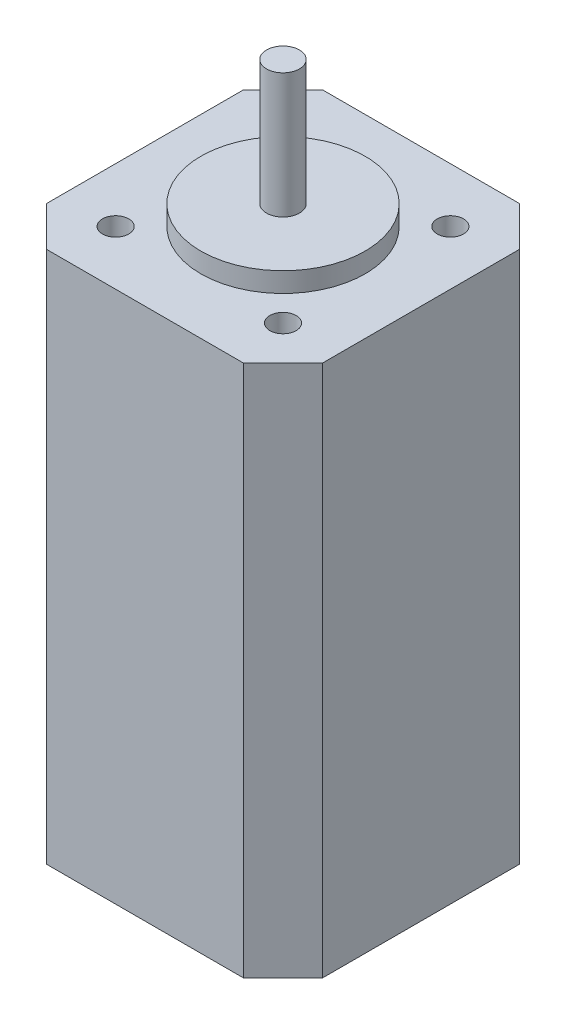
SolidWorks part; units mm, degrees
ref_plane "Płaszczyzna przednia" through (0, 0, 0) normal (0, 0, 1) x (1, 0, 0)
ref_plane "Płaszczyzna górna" through (0, 0, 0) normal (0, 1, 0) x (1, 0, 0)
ref_plane "Płaszczyzna prawa" through (0, 0, 0) normal (1, 0, 0) x (0, 0, -1)
sketch "Szkic1" plane through (0, 0, 0) normal (0, 1, 0) x (1, 0, 0)
  line L0 (21, 21) -> (33.7279, 33.7279)
  line L1 (6, 0) -> (36, 0)
  line L2 (0, 6) -> (0, 36)
  line L3 (6, 42) -> (36, 42)
  line L4 (42, 6) -> (42, 36)
  line L5 (0, 36) -> (6, 42)
  line L6 (36, 42) -> (42, 36)
  line L7 (36, 0) -> (42, 6)
  line L8 (0, 6) -> (6, 0)
  circle A0 centre (21, 21) radius 18
  circle A1 centre (33.7279, 33.7279) radius 2
  circle A2 centre (33.7279, 8.2721) radius 2
  circle A3 centre (8.2721, 8.2721) radius 2
  circle A4 centre (8.2721, 33.7279) radius 2
  point P1 (0, 0)
  point P2 (42, 42)
  point P3 (0, 42)
  point P4 (42, 0)
  point P18 (21, 21)
  dimension "D1" = 4
extrude "Dodanie-wyciągnięcie1" add sketch "Szkic1" along normal blind 81
sketch "Szkic2" plane through (0, 81, 0) normal (0, 1, 0) x (1, 0, 0)
  line L1 (42, 42) -> (21, 42)
  line L2 (42, 42) -> (42, 21)
  line L3 (42, 21) -> (21, 21)
  line L4 (21, 42) -> (21, 21)
  circle A0 centre (21, 21) radius 12.5
extrude "Dodanie-wyciągnięcie2" add sketch "Szkic2" along normal blind 3 contours L4 A0 L3 | L3 A0 L4
sketch "Szkic3" plane through (0, 84, 0) normal (0, 1, 0) x (1, 0, 0)
  circle A1 centre (21, 21) radius 2.5
extrude "Dodanie-wyciągnięcie3" add sketch "Szkic3" along normal blind 19
